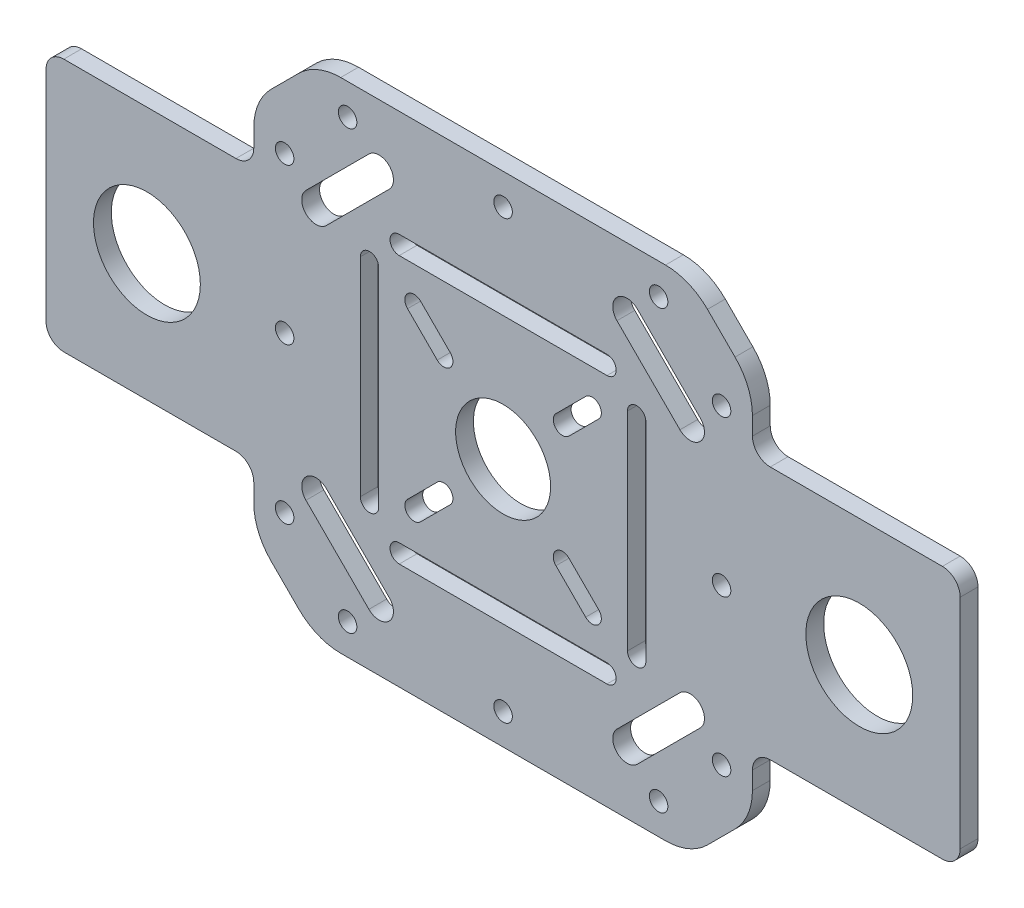
SolidWorks part; units mm, degrees
ref_plane "前视基准面" through (0, 0, 0) normal (0, 0, 1) x (1, 0, 0)
ref_plane "上视基准面" through (0, 0, 0) normal (0, 1, 0) x (1, 0, 0)
ref_plane "右视基准面" through (0, 0, 0) normal (1, 0, 0) x (0, 0, -1)
other "Configuration Table"
sketch "草图1" plane through (0, 0, 0) normal (0, 0, 1) x (1, 0, 0)
  line L0 (-36.8033, 26.1967) -> (-26.1967, 36.8033) construction
  line L7 (0, -46.2) -> (0, 46.2) construction
  line L8 (-31.5, 31.5) -> (31.5, 31.5) construction
  line L9 (46.2, 0) -> (-46.2, 0) construction
  line L10 (-31.5, 31.5) -> (-31.5, -31.5) construction
  line L11 (-31.5, -31.5) -> (31.5, -31.5) construction
  line L21 (31.5, 31.5) -> (31.5, -31.5) construction
  line L22 (-31.5, 31.5) -> (31.5, -31.5) construction
  line L23 (-31.5, -31.5) -> (31.5, 31.5) construction
  line L24 (-26.1967, 36.8033) -> (26.1967, 36.8033) construction
  line L25 (-17.5, 22.5) -> (17.5, 22.5) construction
  line L26 (-17.5, 22.5) -> (17.5, 22.5) construction
  line L31 (-17.5, -22.5) -> (17.5, -22.5) construction
  line L32 (-17.5, 24.05) -> (17.5, 24.05)
  line L33 (-17.5, 20.95) -> (17.5, 20.95)
  line L34 (-17.5, -24.05) -> (17.5, -24.05)
  line L35 (-17.5, -20.95) -> (17.5, -20.95)
  line L36 (-15, 15) -> (15, 15) construction
  line L37 (22.5, -17.5) -> (22.5, 17.5) construction
  line L38 (24.05, -17.5) -> (24.05, 17.5)
  line L39 (20.95, -17.5) -> (20.95, 17.5)
  line L40 (-22.5, -17.5) -> (-22.5, 17.5) construction
  line L41 (-24.05, -17.5) -> (-24.05, 17.5)
  line L42 (-20.95, -17.5) -> (-20.95, 17.5)
  line L43 (-10, 10) -> (10, 10) construction
  line L44 (-10, 10) -> (-10, -10) construction
  line L45 (-10, -10) -> (10, -10) construction
  line L46 (10, 10) -> (10, -10) construction
  line L47 (-10, 10) -> (10, -10) construction
  line L48 (-10, -10) -> (10, 10) construction
  line L49 (-15, 15) -> (-15, -15) construction
  line L50 (-15, -15) -> (15, -15) construction
  line L51 (15, 15) -> (15, -15) construction
  line L52 (10, 10) -> (15, 15) construction
  line L53 (8.904, 11.096) -> (13.904, 16.096)
  line L54 (11.096, 8.904) -> (16.096, 13.904)
  line L55 (-10, 10) -> (-15, 15) construction
  line L56 (-8.904, 11.096) -> (-13.904, 16.096)
  line L57 (-11.096, 8.904) -> (-16.096, 13.904)
  line L58 (-10, -10) -> (-15, -15) construction
  line L59 (-8.904, -11.096) -> (-13.904, -16.096)
  line L60 (-11.096, -8.904) -> (-16.096, -13.904)
  line L61 (10, -10) -> (15, -15) construction
  line L62 (8.904, -11.096) -> (13.904, -16.096)
  line L63 (11.096, -8.904) -> (16.096, -13.904)
  line L64 (-27.3579, 42) -> (27.3579, 42)
  line L67 (-27.3579, -42) -> (27.3579, -42)
  line L68 (-39.0711, 34.4289) -> (-34.4289, 39.0711)
  line L69 (34.4289, 39.0711) -> (39.0711, 34.4289)
  line L70 (39.0711, -34.4289) -> (34.4289, -39.0711)
  line L71 (-34.4289, -39.0711) -> (-39.0711, -34.4289)
  line L72 (42, 27.3579) -> (42, 24.3579)
  line L73 (42, -27.3579) -> (42, -24.3579)
  line L74 (45, 21.3579) -> (74, 21.3579)
  line L75 (45, -21.3579) -> (74, -21.3579)
  line L76 (77, -18.3579) -> (77, 18.3579)
  line L77 (-42, -27.3579) -> (-42, -24.3579)
  line L78 (-45, -21.3579) -> (-74, -21.3579)
  line L79 (-77, -18.3579) -> (-77, 18.3579)
  line L80 (-45, 21.3579) -> (-74, 21.3579)
  line L81 (-42, 27.3579) -> (-42, 24.3579)
  line L82 (-60, 0) -> (60, 0) construction
  line L83 (-31.5, 20.8934) -> (-20.8934, 31.5) construction
  line L84 (-31.5, 20.8934) -> (-20.8934, 31.5) construction
  line L85 (-33.2111, 22.6045) -> (-22.6045, 33.2111)
  line L86 (-29.7889, 19.1823) -> (-19.1823, 29.7889)
  line L87 (31.5, 20.8934) -> (20.8934, 31.5) construction
  line L88 (33.2111, 22.6045) -> (22.6045, 33.2111)
  line L89 (29.7889, 19.1823) -> (19.1823, 29.7889)
  line L90 (-31.5, -20.8934) -> (-20.8934, -31.5) construction
  line L91 (-33.2111, -22.6045) -> (-22.6045, -33.2111)
  line L92 (-29.7889, -19.1823) -> (-19.1823, -29.7889)
  line L93 (31.5, -20.8934) -> (20.8934, -31.5) construction
  line L94 (33.2111, -22.6045) -> (22.6045, -33.2111)
  line L95 (29.7889, -19.1823) -> (19.1823, -29.7889)
  circle A20 centre (0, 0) radius 8
  arc A21 (-17.5, 24.05) -> (-17.5, 20.95) centre (-17.5, 22.5) ccw
  arc A22 (17.5, 20.95) -> (17.5, 24.05) centre (17.5, 22.5) ccw
  arc A23 (-17.5, -24.05) -> (-17.5, -20.95) centre (-17.5, -22.5) cw
  arc A24 (17.5, -20.95) -> (17.5, -24.05) centre (17.5, -22.5) cw
  arc A25 (24.05, -17.5) -> (20.95, -17.5) centre (22.5, -17.5) cw
  arc A26 (20.95, 17.5) -> (24.05, 17.5) centre (22.5, 17.5) cw
  arc A27 (-24.05, -17.5) -> (-20.95, -17.5) centre (-22.5, -17.5) ccw
  arc A28 (-20.95, 17.5) -> (-24.05, 17.5) centre (-22.5, 17.5) ccw
  arc A29 (8.904, 11.096) -> (11.096, 8.904) centre (10, 10) ccw
  arc A30 (16.096, 13.904) -> (13.904, 16.096) centre (15, 15) ccw
  arc A31 (-8.904, 11.096) -> (-11.096, 8.904) centre (-10, 10) cw
  arc A32 (-16.096, 13.904) -> (-13.904, 16.096) centre (-15, 15) cw
  arc A33 (-8.904, -11.096) -> (-11.096, -8.904) centre (-10, -10) ccw
  arc A34 (-16.096, -13.904) -> (-13.904, -16.096) centre (-15, -15) ccw
  arc A35 (8.904, -11.096) -> (11.096, -8.904) centre (10, -10) cw
  arc A36 (16.096, -13.904) -> (13.904, -16.096) centre (15, -15) cw
  circle A37 centre (-26.1967, 36.8033) radius 1.56
  circle A38 centre (-36.8033, 26.1967) radius 1.56
  circle A39 centre (26.1967, 36.8033) radius 1.56
  circle A40 centre (36.8033, 26.1967) radius 1.56
  circle A41 centre (36.8033, -26.1967) radius 1.56
  circle A42 centre (26.1967, -36.8033) radius 1.56
  circle A43 centre (-26.1967, -36.8033) radius 1.56
  circle A44 centre (-36.8033, -26.1967) radius 1.56
  circle A45 centre (0, 36.8033) radius 1.56
  circle A46 centre (36.8033, 0) radius 1.56
  circle A47 centre (0, -36.8033) radius 1.56
  circle A48 centre (-36.8033, 0) radius 1.56
  arc A49 (-27.3579, 42) -> (-34.4289, 39.0711) centre (-27.3579, 32) ccw
  arc A50 (-42, 27.3579) -> (-39.0711, 34.4289) centre (-32, 27.3579) cw
  arc A51 (-42, -27.3579) -> (-39.0711, -34.4289) centre (-32, -27.3579) ccw
  arc A52 (-27.3579, -42) -> (-34.4289, -39.0711) centre (-27.3579, -32) cw
  arc A53 (27.3579, -42) -> (34.4289, -39.0711) centre (27.3579, -32) ccw
  arc A54 (42, -27.3579) -> (39.0711, -34.4289) centre (32, -27.3579) cw
  arc A55 (42, 27.3579) -> (39.0711, 34.4289) centre (32, 27.3579) ccw
  arc A56 (27.3579, 42) -> (34.4289, 39.0711) centre (27.3579, 32) cw
  arc A57 (-45, 21.3579) -> (-42, 24.3579) centre (-45, 24.3579) ccw
  arc A58 (-42, -24.3579) -> (-45, -21.3579) centre (-45, -24.3579) ccw
  arc A59 (42, -24.3579) -> (45, -21.3579) centre (45, -24.3579) cw
  arc A60 (42, 24.3579) -> (45, 21.3579) centre (45, 24.3579) ccw
  arc A61 (74, 21.3579) -> (77, 18.3579) centre (74, 18.3579) cw
  arc A62 (74, -21.3579) -> (77, -18.3579) centre (74, -18.3579) ccw
  arc A63 (-74, -21.3579) -> (-77, -18.3579) centre (-74, -18.3579) cw
  arc A64 (-77, 18.3579) -> (-74, 21.3579) centre (-74, 18.3579) cw
  circle A65 centre (-60, 0) radius 9
  circle A66 centre (60, 0) radius 9
  arc A67 (-33.2111, 22.6045) -> (-29.7889, 19.1823) centre (-31.5, 20.8934) ccw
  arc A68 (-19.1823, 29.7889) -> (-22.6045, 33.2111) centre (-20.8934, 31.5) ccw
  arc A69 (33.2111, 22.6045) -> (29.7889, 19.1823) centre (31.5, 20.8934) cw
  arc A70 (19.1823, 29.7889) -> (22.6045, 33.2111) centre (20.8934, 31.5) cw
  arc A71 (-33.2111, -22.6045) -> (-29.7889, -19.1823) centre (-31.5, -20.8934) cw
  arc A72 (-19.1823, -29.7889) -> (-22.6045, -33.2111) centre (-20.8934, -31.5) cw
  arc A73 (33.2111, -22.6045) -> (29.7889, -19.1823) centre (31.5, -20.8934) ccw
  arc A74 (19.1823, -29.7889) -> (22.6045, -33.2111) centre (20.8934, -31.5) ccw
  point P0 (0, 0)
  point P11 (-31.5, 31.5)
  point P46 (-31.5, 42)
  point P49 (-42, 31.5)
  point P52 (-42, -31.5)
  point P55 (-31.5, -42)
  point P58 (31.5, -42)
  point P61 (42, -31.5)
  point P64 (42, 31.5)
  point P73 (0, 22.5)
  point P78 (0, -22.5)
  point P86 (22.5, 0)
  point P93 (-22.5, 0)
  point P105 (12.5, 12.5)
  point P110 (-12.5, 12.5)
  point P115 (-12.5, -12.5)
  point P120 (12.5, -12.5)
  point P125 (31.5, 42)
  point P136 (-42, 21.3579)
  point P139 (-42, -21.3579)
  point P142 (42, -21.3579)
  point P145 (42, 21.3579)
  point P148 (77, 21.3579)
  point P151 (77, -21.3579)
  point P154 (-77, -21.3579)
  point P157 (-77, 21.3579)
  point P160 (0, 0)
  point P162 (-26.1967, 26.1967)
  point P165 (-26.1967, 26.1967)
  point P172 (26.1967, 26.1967)
  point P179 (-26.1967, -26.1967)
  point P186 (26.1967, -26.1967)
  dimension "D2" = 3.12
  dimension "D3" = 52.3934
  dimension "D4" = 10
  dimension "D6" = 3
  dimension "D1" = 15
extrude "凸台-拉伸1" add sketch "草图1" along normal blind 3
